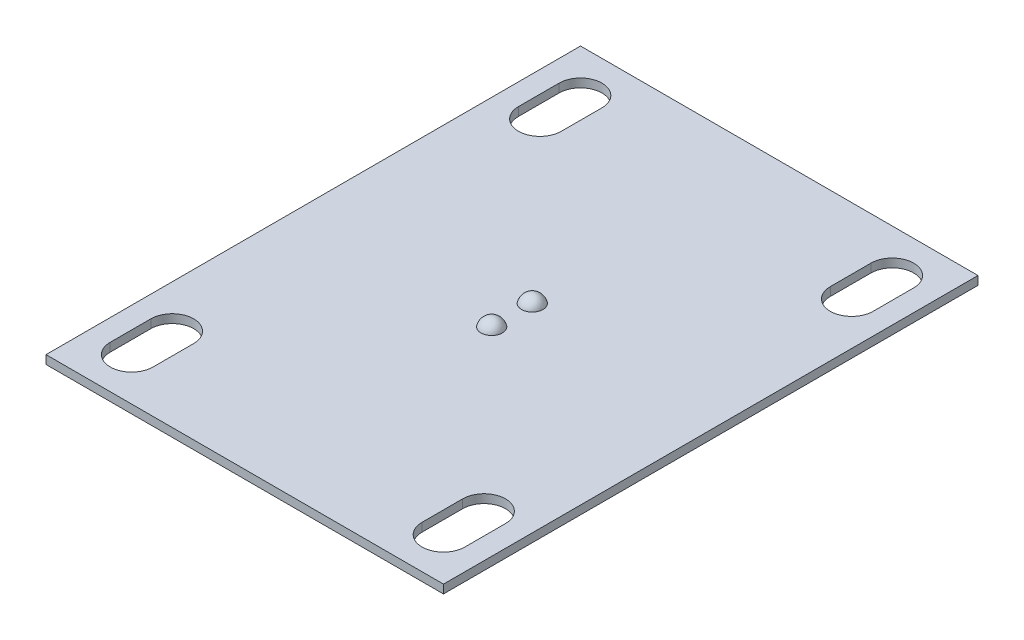
SolidWorks part; units mm, degrees
ref_plane "Front Plane" through (0, 0, 0) normal (0, 0, 1) x (1, 0, 0)
ref_plane "Top Plane" through (0, 0, 0) normal (0, 1, 0) x (1, 0, 0)
ref_plane "Right Plane" through (0, 0, 0) normal (1, 0, 0) x (0, 0, -1)
sketch "Sketch1" plane through (0, -2.3, 0) normal (0, -1, 0) x (-1, 0, 0)
  line L0 (-47.4, 47.0488) -> (-47.4, 47.1488) construction
  line L1 (45.4, -77.7512) -> (-47.4, -77.7512)
  line L2 (45.4, -77.7512) -> (45.4, 47.0488)
  line L3 (45.4, 47.0488) -> (-47.4, 47.0488)
  line L4 (-47.4, -77.7512) -> (-47.4, 47.0488)
  line L5 (-47.5, 47.1488) -> (45.5, 47.1488) construction
  line L6 (-47.4, 47.0488) -> (-47.5, 47.0488) construction
  line L7 (-47.5, 7.6488) -> (-47.5, 47.1488) construction
  line L9 (45.4, -77.7512) -> (45.5, -77.7512) construction
  line L10 (45.5, -77.8512) -> (45.5, -38.3512) construction
  line L11 (45.4, -77.7512) -> (45.4, -77.8512) construction
  line L12 (-47.5, -77.8512) -> (45.5, -77.8512) construction
  dimension "D1" = 0.1
extrude "Boss-Extrude1" add sketch "Sketch1" along normal blind 2
sketch "Sketch2" plane through (0, -2.3, 0) normal (0, 1, 0) x (1, 0, 0)
  line L0 (0, 0) -> (1, -10.618) construction
  line L1 (1, -10.618) -> (1, -20.1012) construction
  line L2 (-45.4, 3.8723) -> (47.4, 3.8723) construction
  line L3 (-45.4, -77.7512) -> (-45.4, 47.0488) construction
  line L4 (47.4, 47.0488) -> (47.4, -77.7512) construction
  line L5 (1, 3.8723) -> (1, -10.618) construction
  point P13 (1, -20.1012)
  dimension "D1" = 10.618
  dimension "D2" = 1
  dimension "D3" = 9.4832
ref_plane "Plane1" through (1, 0, 0) normal (-1, 0, 0) x (0, 0, 1)
sketch "Sketch3" plane through (1, 0, 0) normal (-1, 0, 0) x (0, 0, 1)
  line L0 (0, -2.3) -> (10.618, -2.3) construction
  line L1 (10.618, -2.3) -> (20.1012, -2.3) construction
  line L2 (10.618, -0.3) -> (8.3365, -0.3) construction
  line L3 (8.118, -2.3) -> (10.618, -2.3)
  line L4 (10.618, -0.3) -> (10.618, -2.3)
  arc A0 (8.118, -2.3) -> (10.618, -0.3) centre (10.618, -2.8625) cw
  dimension "D1" = 2
  dimension "D2" = 2.5
revolve "Revolve2" add sketch "Sketch3" angle 360 about L4
sketch "Sketch5" plane through (1, 0, 0) normal (-1, 0, 0) x (0, 0, 1)
  line L0 (20.1012, -2.3) -> (20.1012, -0.3)
  line L1 (10.618, -2.3) -> (20.1012, -2.3) construction
  line L2 (77.7512, -2.3) -> (-47.0488, -2.3) construction
  line L3 (10.618, -0.3) -> (10.618, -2.3) construction
  line L4 (20.1012, -2.3) -> (17.6012, -2.3)
  line L5 (8.118, -2.3) -> (10.618, -2.3) construction
  line L6 (20.1012, -0.3) -> (16.9161, -0.3) construction
  arc A0 (17.6012, -2.3) -> (20.1012, -0.3) centre (20.1012, -2.8625) cw
revolve "Revolve3" add sketch "Sketch5" angle 360 about L0
ref_plane "Plane2" through (0, 0, 10.618) normal (0, 0, -1) x (-1, 0, 0)
sketch "Sketch7" plane through (0, 0, 10.618) normal (0, 0, -1) x (-1, 0, 0)
  line L0 (-3.5, -2.3) -> (1.5, -2.3)
  arc A0 (1.5, -2.3) -> (-3.5, -2.3) centre (-1, -2.8625) ccw
  arc A1 (1.5, -2.3) -> (-3.5, -2.3) centre (-1, -2.8625) ccw construction
extrude "Boss-Extrude2" [suppressed] add sketch "Sketch7" against normal up to vertex
sketch "Sketch6" plane through (0, -2.3, 0) normal (0, 1, 0) x (1, 0, 0)
  line L0 (-35.4, 37.0488) -> (-35.4, 27.5656) construction
  line L1 (-30.4, 37.0488) -> (-30.4, 27.5656)
  line L2 (-40.4, 37.0488) -> (-40.4, 27.5656)
  line L3 (-35.4, -58.268) -> (-35.4, -67.7512) construction
  line L4 (-30.4, -58.268) -> (-30.4, -67.7512)
  line L5 (-40.4, -58.268) -> (-40.4, -67.7512)
  line L6 (-35.4, -67.7512) -> (-45.4, -67.7512) construction
  line L7 (-45.4, -77.7512) -> (-45.4, 47.0488) construction
  line L8 (-35.4, -67.7512) -> (-35.4, -77.7512) construction
  line L9 (47.4, -77.7512) -> (-45.4, -77.7512) construction
  line L10 (-35.4, 37.0488) -> (-35.4, 47.0488) construction
  line L11 (-45.4, 47.0488) -> (47.4, 47.0488) construction
  line L12 (1, -10.618) -> (1, -20.1012) construction
  arc A0 (-30.4, 37.0488) -> (-40.4, 37.0488) centre (-35.4, 37.0488) ccw
  arc A1 (-40.4, 27.5656) -> (-30.4, 27.5656) centre (-35.4, 27.5656) ccw
  arc A2 (-30.4, -58.268) -> (-40.4, -58.268) centre (-35.4, -58.268) ccw
  arc A3 (-40.4, -67.7512) -> (-30.4, -67.7512) centre (-35.4, -67.7512) ccw
  point P2 (-35.4, 32.3072)
  point P7 (-35.4, -63.0096)
  dimension "D2" = 5
  dimension "D1" = 5
extrude "Cut-Extrude1" cut sketch "Sketch6" against normal through all
mirror "Mirror1" about plane through (1, 0, 0) normal (-1, 0, 0) of "Cut-Extrude1"
equation "\"D1@Sketch2\"=10.61798754mm"
equation "\"D3@Sketch2\"=9.48321349mm"
